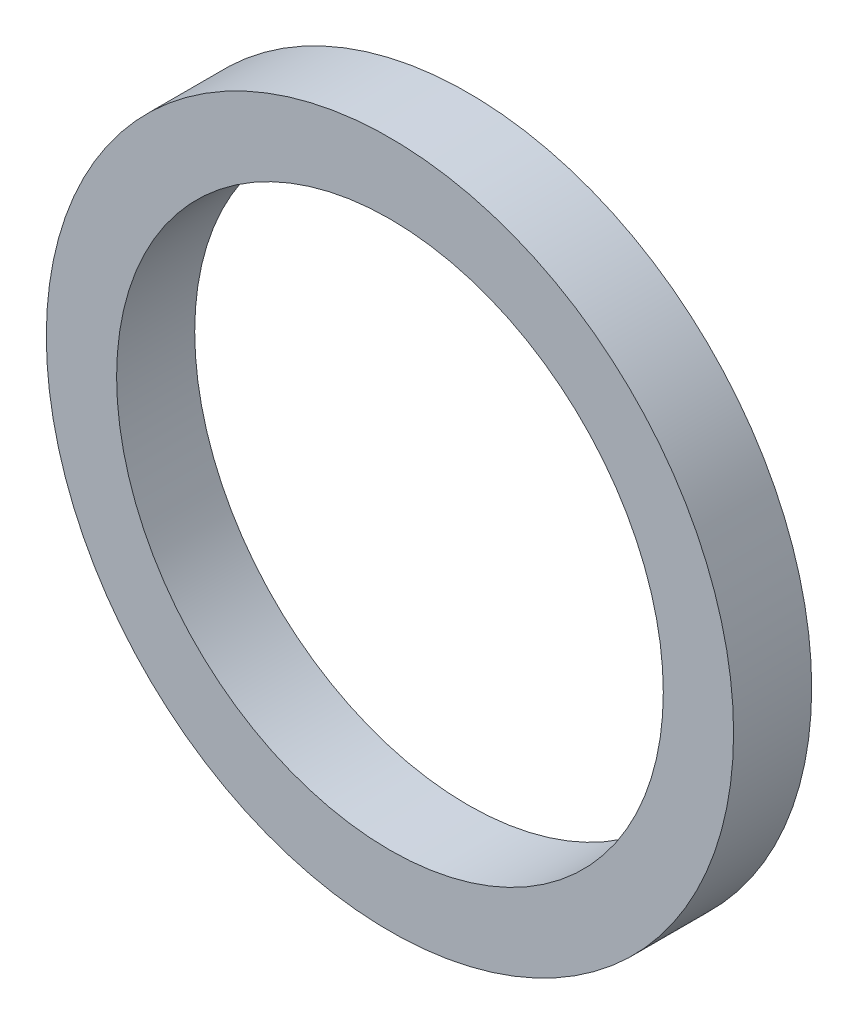
SolidWorks part; units mm, degrees
material "AISI 1020"
ref_plane "Plano frontal" through (0, 0, 0) normal (0, 0, 1) x (1, 0, 0)
ref_plane "Plano superior" through (0, 0, 0) normal (0, 1, 0) x (1, 0, 0)
ref_plane "Plano direito" through (0, 0, 0) normal (1, 0, 0) x (0, 0, -1)
sketch "Esboço1" plane through (0, 0, 0) normal (0, 0, 1) x (1, 0, 0)
  circle A0 centre (0, 0) radius 8.75
  circle A1 centre (0, 0) radius 11
  dimension "D1" = 17.5
  dimension "D2" = 22
extrude "Extrusão1" add sketch "Esboço1" along normal mid plane 2.5
